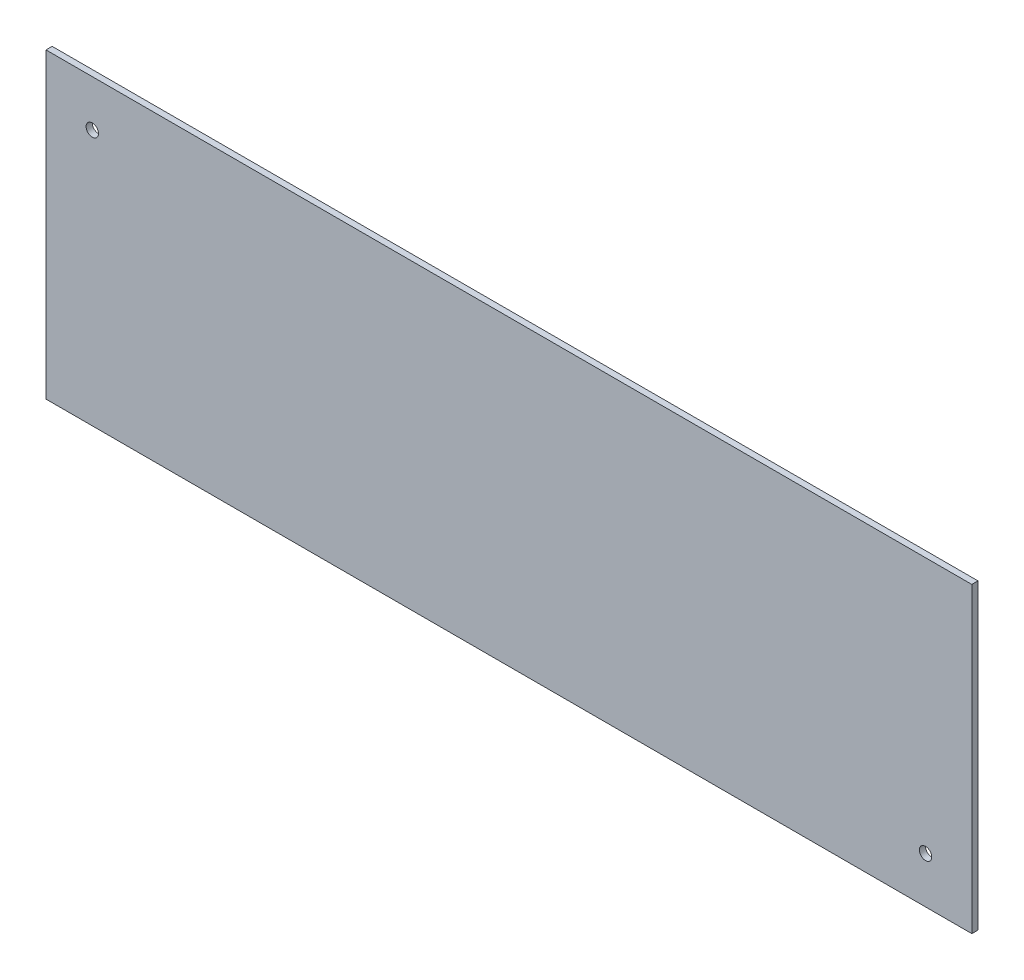
SolidWorks part; units mm, degrees
ref_plane "Front Plane" through (0, 0, 0) normal (0, 0, 1) x (1, 0, 0)
ref_plane "Top Plane" through (0, 0, 0) normal (0, 1, 0) x (1, 0, 0)
ref_plane "Right Plane" through (0, 0, 0) normal (1, 0, 0) x (0, 0, -1)
sketch "Sketch1" plane through (0, 0, 0) normal (0, 0, 1) x (1, 0, 0)
  line L1 (-150, 49) -> (150, 49)
  line L2 (-150, 49) -> (-150, -49)
  line L3 (-150, -49) -> (150, -49)
  line L4 (150, 49) -> (150, -49)
  line L5 (-150, 49) -> (150, -49) construction
  line L6 (-150, -49) -> (150, 49) construction
  point P0 (0, 0)
  dimension "D1" = 98
  dimension "D2" = 300
extrude "Boss-Extrude1" add sketch "Sketch1" along normal blind 2
sketch "Sketch2" plane through (0, 0, 2) normal (0, 0, 1) x (1, 0, 0)
  line L0 (150, 49) -> (-150, 49) construction
  line L1 (-150, 49) -> (-150, -49) construction
  line L2 (-150, -49) -> (150, -49) construction
  line L3 (150, -49) -> (150, 49) construction
  circle A0 centre (-135, 34) radius 2
  circle A1 centre (135, -34) radius 2
  dimension "D1" = 4
  dimension "D2" = 4
  dimension "D3" = 15
  dimension "D4" = 15
  dimension "D5" = 15
  dimension "D6" = 15
extrude "Cut-Extrude1" cut sketch "Sketch2" against normal through all
